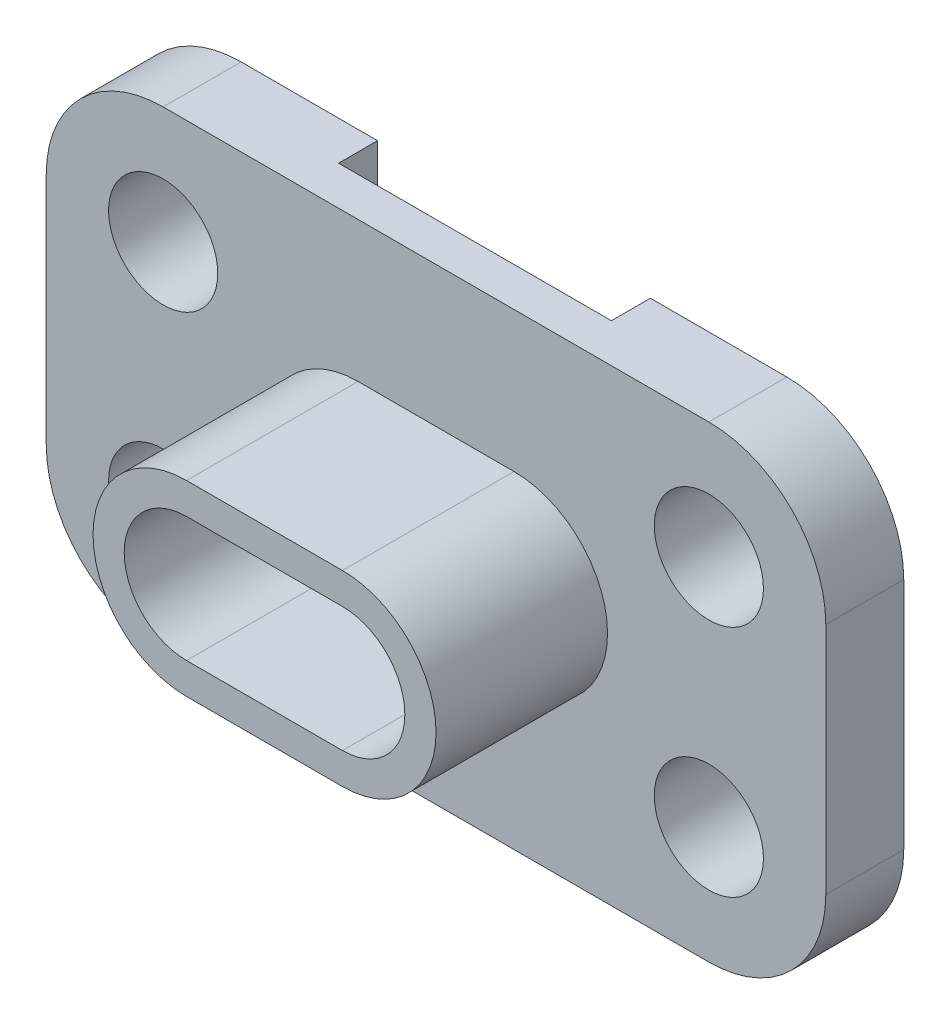
SolidWorks part; units mm, degrees
ref_plane "Front Plane" through (0, 0, 0) normal (0, 0, 1) x (1, 0, 0)
ref_plane "Top Plane" through (0, 0, 0) normal (0, 1, 0) x (1, 0, 0)
ref_plane "Right Plane" through (0, 0, 0) normal (1, 0, 0) x (0, 0, -1)
sketch "Sketch1" plane through (0, 0, 0) normal (0, 0, 1) x (1, 0, 0)
  line L1 (-35, 30) -> (35, 30)
  line L2 (-50, 15) -> (-50, -15)
  line L3 (-35, -30) -> (35, -30)
  line L4 (50, 15) -> (50, -15)
  line L5 (-50, 30) -> (50, -30) construction
  line L6 (-50, -30) -> (50, 30) construction
  arc A0 (50, 15) -> (35, 30) centre (35, 15) ccw
  arc A1 (35, -30) -> (50, -15) centre (35, -15) ccw
  arc A2 (-35, -30) -> (-50, -15) centre (-35, -15) cw
  arc A3 (-50, 15) -> (-35, 30) centre (-35, 15) cw
  point P0 (0, 0)
  dimension "D3" = 15
  dimension "D1" = 100
  dimension "D2" = 60
extrude "Boss-Extrude1" add sketch "Sketch1" along normal blind 10
sketch "Sketch2" plane through (0, -30, 0) normal (0, -1, 0) x (1, 0, 0)
  line L0 (0, 16.0819) -> (0, -14.6657) construction
  line L1 (-17.5, 0) -> (17.5, 0)
  line L2 (-35, 0) -> (35, 0) construction
  line L3 (17.5, 0) -> (17.5, 5)
  line L4 (17.5, 5) -> (-17.5, 5)
  line L5 (-17.5, 5) -> (-17.5, 0)
  line L6 (-35, 10) -> (35, 10) construction
  point P8 (0, 0)
  dimension "D1" = 35
  dimension "D2" = 5
extrude "Cut-Extrude1" cut sketch "Sketch2" against normal up to next
sketch "Sketch3" plane through (0, 0, 10) normal (0, 0, 1) x (1, 0, 0)
  line L0 (0, 30) -> (0, -30) construction
  line L1 (35, 30) -> (-35, 30) construction
  line L2 (-35, -30) -> (35, -30) construction
  line L3 (-50, 0) -> (50, 0) construction
  line L4 (-50, 15) -> (-50, -15) construction
  line L5 (50, -15) -> (50, 15) construction
  circle A0 centre (-35, 15) radius 7
  circle A2 centre (35, 15) radius 7
  circle A4 centre (35, -15) radius 7
  circle A5 centre (-35, -15) radius 7
  point P14 (0, 0)
  dimension "D3" = 14
  dimension "D4" = 14
  dimension "D1" = 35
  dimension "D2" = 70
  dimension "D5" = 15
extrude "Cut-Extrude2" cut sketch "Sketch3" against normal up to next
sketch "Sketch4" plane through (0, 0, 10) normal (0, 0, 1) x (1, 0, 0)
  line L0 (-10, 0) -> (10, 0) construction
  line L1 (-10, 12) -> (10, 12)
  line L2 (-10, -12) -> (10, -12)
  arc A0 (-10, 12) -> (-10, -12) centre (-10, 0) ccw
  arc A1 (10, -12) -> (10, 12) centre (10, 0) ccw
  point P2 (0, 0)
  dimension "D1" = 20
  dimension "D2" = 24
extrude "Boss-Extrude2" add sketch "Sketch4" along normal blind 22
sketch "Sketch5" plane through (0, 0, 32) normal (0, 0, 1) x (1, 0, 0)
  line L0 (-10, 0) -> (10, 0) construction
  line L1 (-10, 8) -> (10, 8)
  line L2 (-10, -8) -> (10, -8)
  arc A0 (-10, 8) -> (-10, -8) centre (-10, 0) ccw
  arc A1 (10, -8) -> (10, 8) centre (10, 0) ccw
  point P2 (0, 0)
  dimension "D1" = 20
  dimension "D2" = 16
extrude "Cut-Extrude3" cut sketch "Sketch5" against normal blind 22
